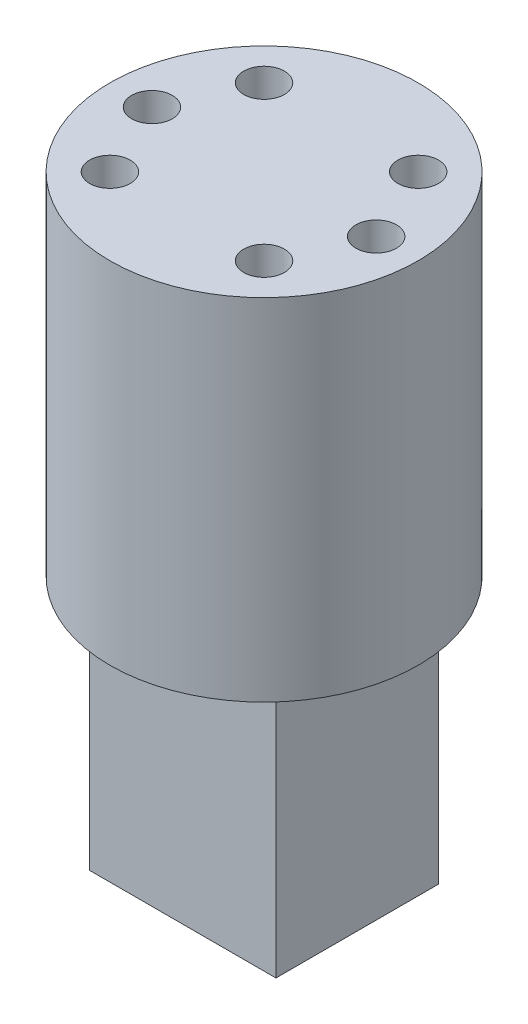
SolidWorks part; units mm, degrees
ref_plane "Front Plane" through (0, 0, 0) normal (0, 0, 1) x (1, 0, 0)
ref_plane "Top Plane" through (0, 0, 0) normal (0, 1, 0) x (1, 0, 0)
ref_plane "Right Plane" through (0, 0, 0) normal (1, 0, 0) x (0, 0, -1)
sketch "Sketch2" plane through (0, 0, 0) normal (0, 1, 0) x (1, 0, 0)
  circle A0 centre (0, 0) radius 11
  dimension "D1" = 22
extrude "Boss-Extrude1" add sketch "Sketch2" against normal blind 25
sketch "Sketch3" plane through (0, -25, 0) normal (0, -1, 0) x (1, 0, 0)
  line L1 (-6.65, 5.8) -> (6.65, 5.8)
  line L2 (-6.65, 5.8) -> (-6.65, -5.8)
  line L3 (-6.65, -5.8) -> (6.65, -5.8)
  line L4 (6.65, 5.8) -> (6.65, -5.8)
  line L5 (-6.65, 5.8) -> (6.65, -5.8) construction
  line L6 (-6.65, -5.8) -> (6.65, 5.8) construction
  point P0 (0, 0)
  dimension "D1" = 13.3
  dimension "D2" = 11.6
extrude "Boss-Extrude2" add sketch "Sketch3" along normal offset from surface (18.6 mm away) 43.6 up to face at (0, 0, 11)
sketch "Sketch4" plane through (0, 0, 0) normal (0, 0, 1) x (1, 0, 0)
  line L0 (-2.5, -43.6) -> (0, -45.6)
  line L1 (-6.65, -43.6) -> (6.65, -43.6) construction
  line L2 (0, -45.6) -> (0, -43.6)
  line L3 (0, -43.6) -> (-2.5, -43.6)
  dimension "D1" = 45.6
  dimension "D2" = 2.5
revolve "Revolve1" add sketch "Sketch4" angle 360 about L2
sketch "Sketch5" plane through (0, 0, 0) normal (0, 1, 0) x (1, 0, 0)
  line L12 (-5.5, 5.5) -> (5.5, 5.5) construction
  line L13 (-5.5, 5.5) -> (-5.5, -5.5) construction
  line L14 (-5.5, -5.5) -> (5.5, -5.5) construction
  line L15 (5.5, 5.5) -> (5.5, -5.5) construction
  line L16 (-8, 0) -> (8, 0) construction
  point P72 (-5.5, 5.5)
  point P73 (5.5, -5.5)
  point P140 (-5.5, -5.5)
  point P141 (5.5, 5.5)
  point P143 (0, 5.5)
  point P145 (5.5, 0)
  point P152 (8, 0)
  point P176 (-8, 0)
  point P177 (0, 0)
  dimension "D1" = 11
  dimension "D2" = 16
hole_wizard "M2.5 Clearance Hole1" positions "Sketch5" profile "Sketch7" hole size "M2.5" standard "ANSI Metric"
sketch "Sketch7" plane through (-5.5, 0, -5.5) normal (1, 0, 0) x (0, 0, 1)
  line L0 (0, 0) -> (0, 5.8712)
  line L1 (0, 5.8712) -> (1.45, 5)
  line L2 (1.45, 5) -> (1.45, 0)
  line L5 (1.45, 0) -> (0, 0)
  line L10 (0, 5.8712) -> (-1.45, 5) construction
  line L11 (0, -6.35) -> (0, 107.95) construction
  dimension "Hole Dia." = 2.9
  dimension "Hole Depth" = 5
  dimension "Drill Angle" = 118
